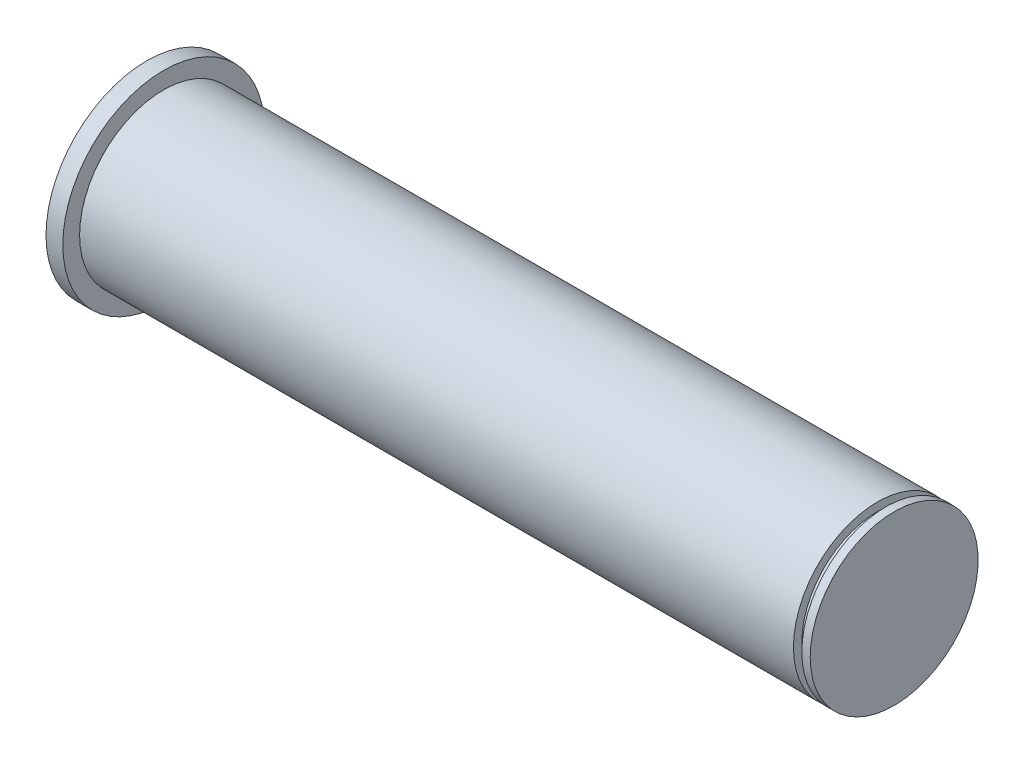
SolidWorks part; units mm, degrees
ref_plane "Front Plane" through (0, 0, 0) normal (0, 0, 1) x (1, 0, 0)
ref_plane "Top Plane" through (0, 0, 0) normal (0, 1, 0) x (1, 0, 0)
ref_plane "Right Plane" through (0, 0, 0) normal (1, 0, 0) x (0, 0, -1)
sketch "Sketch1" plane through (0, 0, 0) normal (0, 0, 1) x (1, 0, 0)
  line L0 (0, 0) -> (0, 12)
  line L1 (0, 12) -> (2, 12)
  line L2 (2, 12) -> (2, 10)
  line L3 (2, 10) -> (87, 10)
  line L4 (87, 10) -> (87, 9)
  line L5 (87, 9) -> (88, 9)
  line L6 (88, 9) -> (88, 10)
  line L7 (88, 10) -> (89, 10)
  line L8 (89, 10) -> (89, 0)
  line L9 (89, 0) -> (0, 0)
  line L10 (0, 0) -> (89, 0) construction
  dimension "D1" = 85
  dimension "D2" = 1
  dimension "D3" = 1
  dimension "D4" = 10
  dimension "D5" = 2
  dimension "D6" = 2
  dimension "D7" = 1
revolve "Revolve1" add sketch "Sketch1" angle 360 about L10
